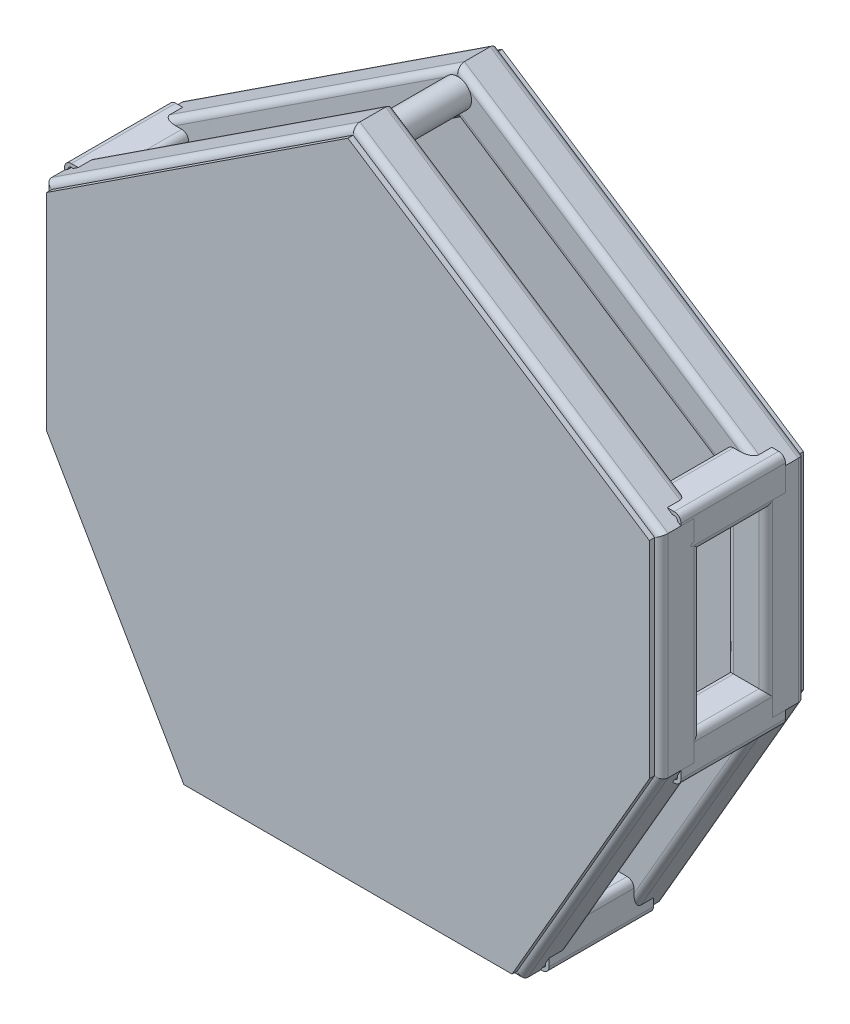
SolidWorks part; units mm, degrees
ref_plane "Front Plane" through (0, 0, 0) normal (0, 0, 1) x (1, 0, 0)
ref_plane "Top Plane" through (0, 0, 0) normal (0, 1, 0) x (1, 0, 0)
ref_plane "Right Plane" through (0, 0, 0) normal (1, 0, 0) x (0, 0, -1)
sketch "Sketch2" plane through (0, 0, 0) normal (0, 0, 1) x (1, 0, 0)
  line L7 (-356.066, 268.7117) -> (-135.0297, 413.7117)
  line L8 (-15.0297, -56.2883) -> (-255.0297, -56.2883)
  line L9 (86.0066, 118.7117) -> (86.0066, 268.7117)
  line L11 (-356.066, 118.7117) -> (-356.066, 268.7117)
  line L12 (-135.0297, 413.7117) -> (86.0066, 268.7117)
  line L13 (86.0066, 268.7117) -> (86.0066, 118.7117)
  line L14 (86.0066, 118.7117) -> (-15.0297, -56.2883)
  line L15 (-356.066, 268.7117) -> (-356.066, 118.7117)
  line L16 (-356.066, 118.7117) -> (-255.0297, -56.2883)
  dimension "D1" = 175
  dimension "D2" = 175
  dimension "D3" = 60
  dimension "D4" = 60
  dimension "D5" = 240
  dimension "D6" = 101.0363
  dimension "D7" = 150
  dimension "D8" = 150
  dimension "D9" = 470
ref_plane "Plane1" through (0, 0, 80) normal (0, 0, 1) x (1, 0, 0)
sketch "Sketch3" plane through (0, 0, 80) normal (0, 0, 1) x (1, 0, 0)
  line L0 (-135.0297, 413.7117) -> (86.0066, 268.7117) construction
  line L1 (86.0066, 118.7117) -> (86.0066, 268.7117) construction
  line L2 (86.0066, 118.7117) -> (-15.0297, -56.2883) construction
  line L3 (-15.0297, -56.2883) -> (-255.0297, -56.2883) construction
  line L4 (-356.066, 118.7117) -> (-255.0297, -56.2883) construction
  line L5 (-356.066, 118.7117) -> (-356.066, 268.7117) construction
  line L6 (-356.066, 268.7117) -> (-135.0297, 413.7117) construction
  line L7 (-135.0297, 413.7117) -> (86.0066, 268.7117)
  line L8 (86.0066, 118.7117) -> (86.0066, 268.7117)
  line L9 (86.0066, 118.7117) -> (-15.0297, -56.2883)
  line L10 (-15.0297, -56.2883) -> (-255.0297, -56.2883)
  line L11 (-356.066, 118.7117) -> (-255.0297, -56.2883)
  line L12 (-356.066, 118.7117) -> (-356.066, 268.7117)
  line L13 (-356.066, 268.7117) -> (-135.0297, 413.7117)
  dimension "D1" = 175
sketch3d "3DSketch1"
  line L0 (-356.066, 268.7117, 80) -> (-356.066, 268.7117, 0)
  line L1 (-356.066, 268.7117, 80) -> (-135.0297, 413.7117, 80) construction
  line L2 (-356.066, 118.7117, 80) -> (-356.066, 268.7117, 80) construction
  line L3 (-356.066, 118.7117, 0) -> (-356.066, 268.7117, 0) construction
  line L6 (86.0066, 118.7117, 0) -> (86.0066, 118.7117, 80)
  line L7 (-15.0297, -56.2883, 80) -> (-15.0297, -56.2883, 0)
  line L8 (-356.066, 118.7117, 80) -> (-356.066, 118.7117, 0)
  line L9 (86.0066, 268.7117, 80) -> (86.0066, 268.7117, 0)
  line L10 (-255.0297, -56.2883, 80) -> (-255.0297, -56.2883, 0)
  line L11 (-135.0297, 413.7117, 0) -> (-135.0297, 413.7117, 80)
other "Square tube 30 X 30 X 2.6(1)"
ref_plane "Plane2" through (-15.0297, -56.2883, 80) normal (-1, 0, 0) x (0, -1, 0)
sketch "Sketch1" plane through (-15.0297, -56.2883, 80) normal (-1, 0, 0) x (0, -1, 0)
  line L0 (-9.8, -12.4) -> (9.8, -12.4)
  line L1 (-12.4, -9.8) -> (-12.4, 9.8)
  line L2 (9.8, 12.4) -> (-9.8, 12.4)
  line L3 (12.4, 9.8) -> (12.4, -9.8)
  line L4 (-9.8, -15) -> (9.8, -15)
  line L5 (-15, -9.8) -> (-15, 9.8)
  line L6 (9.8, 15) -> (-9.8, 15)
  line L7 (15, 9.8) -> (15, -9.8)
  arc A0 (15, 9.8) -> (9.8, 15) centre (9.8, 9.8) ccw
  arc A1 (9.8, -15) -> (15, -9.8) centre (9.8, -9.8) ccw
  arc A2 (-15, -9.8) -> (-9.8, -15) centre (-9.8, -9.8) ccw
  arc A3 (-9.8, 15) -> (-15, 9.8) centre (-9.8, 9.8) ccw
  arc A4 (-9.8, 12.4) -> (-12.4, 9.8) centre (-9.8, 9.8) ccw
  arc A5 (12.4, 9.8) -> (9.8, 12.4) centre (9.8, 9.8) ccw
  arc A6 (9.8, -12.4) -> (12.4, -9.8) centre (9.8, -9.8) ccw
  arc A7 (-12.4, -9.8) -> (-9.8, -12.4) centre (-9.8, -9.8) ccw
  point P0 (-15, 0)
  point P1 (15, 0)
  point P2 (0, 15)
  point P3 (0, -15)
  point P4 (0, 0)
  point P5 (-15, -15)
  point P6 (15, -15)
  point P7 (15, 15)
  point P8 (-15, 15)
  point P33 (0, 0)
  dimension "D1" = 5.2
  dimension "Thickness" = 2.6
  dimension "V_leg" = 30
other "Square tube 30 X 30 X 2.6(2)"
ref_plane "Plane3" through (-15.0297, -56.2883, 0) normal (-1, 0, 0) x (0, -1, 0)
sketch "Sketch11" plane through (-15.0297, -56.2883, 0) normal (-1, 0, 0) x (0, -1, 0)
  line L0 (-9.8, -12.4) -> (9.8, -12.4)
  line L1 (-12.4, -9.8) -> (-12.4, 9.8)
  line L2 (9.8, 12.4) -> (-9.8, 12.4)
  line L3 (12.4, 9.8) -> (12.4, -9.8)
  line L4 (-9.8, -15) -> (9.8, -15)
  line L5 (-15, -9.8) -> (-15, 9.8)
  line L6 (9.8, 15) -> (-9.8, 15)
  line L7 (15, 9.8) -> (15, -9.8)
  arc A0 (15, 9.8) -> (9.8, 15) centre (9.8, 9.8) ccw
  arc A1 (9.8, -15) -> (15, -9.8) centre (9.8, -9.8) ccw
  arc A2 (-15, -9.8) -> (-9.8, -15) centre (-9.8, -9.8) ccw
  arc A3 (-9.8, 15) -> (-15, 9.8) centre (-9.8, 9.8) ccw
  arc A4 (-9.8, 12.4) -> (-12.4, 9.8) centre (-9.8, 9.8) ccw
  arc A5 (12.4, 9.8) -> (9.8, 12.4) centre (9.8, 9.8) ccw
  arc A6 (9.8, -12.4) -> (12.4, -9.8) centre (9.8, -9.8) ccw
  arc A7 (-12.4, -9.8) -> (-9.8, -12.4) centre (-9.8, -9.8) ccw
  point P0 (-15, 0)
  point P1 (15, 0)
  point P2 (0, 15)
  point P3 (0, -15)
  point P4 (0, 0)
  point P5 (-15, -15)
  point P6 (15, -15)
  point P7 (15, 15)
  point P8 (-15, 15)
  point P33 (0, 0)
  dimension "D1" = 5.2
  dimension "Thickness" = 2.6
  dimension "V_leg" = 30
other "Square tube 30 X 30 X 2.6(3)"
ref_plane "Plane4" through (-356.066, 118.7117, 80) normal (0, 0, -1) x (1, 0, 0)
sketch "Sketch12" plane through (-356.066, 118.7117, 80) normal (0, 0, -1) x (1, 0, 0)
  line L0 (-9.8, -12.4) -> (9.8, -12.4)
  line L1 (-12.4, -9.8) -> (-12.4, 9.8)
  line L2 (9.8, 12.4) -> (-9.8, 12.4)
  line L3 (12.4, 9.8) -> (12.4, -9.8)
  line L4 (-9.8, -15) -> (9.8, -15)
  line L5 (-15, -9.8) -> (-15, 9.8)
  line L6 (9.8, 15) -> (-9.8, 15)
  line L7 (15, 9.8) -> (15, -9.8)
  arc A0 (15, 9.8) -> (9.8, 15) centre (9.8, 9.8) ccw
  arc A1 (9.8, -15) -> (15, -9.8) centre (9.8, -9.8) ccw
  arc A2 (-15, -9.8) -> (-9.8, -15) centre (-9.8, -9.8) ccw
  arc A3 (-9.8, 15) -> (-15, 9.8) centre (-9.8, 9.8) ccw
  arc A4 (-9.8, 12.4) -> (-12.4, 9.8) centre (-9.8, 9.8) ccw
  arc A5 (12.4, 9.8) -> (9.8, 12.4) centre (9.8, 9.8) ccw
  arc A6 (9.8, -12.4) -> (12.4, -9.8) centre (9.8, -9.8) ccw
  arc A7 (-12.4, -9.8) -> (-9.8, -12.4) centre (-9.8, -9.8) ccw
  point P0 (-15, 0)
  point P1 (15, 0)
  point P2 (0, 15)
  point P3 (0, -15)
  point P4 (0, 0)
  point P5 (-15, -15)
  point P6 (15, -15)
  point P7 (15, 15)
  point P8 (-15, 15)
  point P33 (0, 0)
  dimension "D1" = 5.2
  dimension "Thickness" = 2.6
  dimension "V_leg" = 30
sketch "Sketch14" plane through (0, 0, -15) normal (0, 0, -1) x (-1, 0, 0)
  line L0 (135.0297, 425.4322) -> (365.866, 274.0034) construction
  line L1 (365.866, 274.0034) -> (365.866, 116.0858) construction
  line L2 (365.866, 116.0858) -> (260.6878, -66.0883) construction
  line L3 (260.6878, -66.0883) -> (9.3717, -66.0883) construction
  line L4 (9.3717, -66.0883) -> (-95.8066, 116.0858) construction
  line L5 (-95.8066, 116.0858) -> (-95.8066, 274.0034) construction
  line L6 (-95.8066, 274.0034) -> (135.0297, 425.4322) construction
  line L7 (135.0297, 425.4322) -> (365.866, 274.0034)
  line L8 (365.866, 274.0034) -> (365.866, 116.0858)
  line L9 (365.866, 116.0858) -> (260.6878, -66.0883)
  line L10 (260.6878, -66.0883) -> (9.3717, -66.0883)
  line L11 (9.3717, -66.0883) -> (-95.8066, 116.0858)
  line L12 (-95.8066, 116.0858) -> (-95.8066, 274.0034)
  line L13 (-95.8066, 274.0034) -> (135.0297, 425.4322)
extrude "Boss-Extrude1" add sketch "Sketch14" along normal blind 4 separate body
sketch "Sketch15" plane through (0, 0, 95) normal (0, 0, 1) x (1, 0, 0)
  line L0 (95.8066, 274.0034) -> (-135.0297, 425.4322) construction
  line L1 (95.8066, 116.0858) -> (95.8066, 274.0034) construction
  line L2 (-9.3717, -66.0883) -> (95.8066, 116.0858) construction
  line L3 (-260.6878, -66.0883) -> (-9.3717, -66.0883) construction
  line L4 (-365.866, 116.0858) -> (-260.6878, -66.0883) construction
  line L5 (-365.866, 274.0034) -> (-365.866, 116.0858) construction
  line L6 (-135.0297, 425.4322) -> (-365.866, 274.0034) construction
  line L7 (95.8066, 274.0034) -> (-135.0297, 425.4322)
  line L8 (95.8066, 116.0858) -> (95.8066, 274.0034)
  line L9 (-9.3717, -66.0883) -> (95.8066, 116.0858)
  line L10 (-260.6878, -66.0883) -> (-9.3717, -66.0883)
  line L11 (-365.866, 116.0858) -> (-260.6878, -66.0883)
  line L12 (-365.866, 274.0034) -> (-365.866, 116.0858)
  line L13 (-135.0297, 425.4322) -> (-365.866, 274.0034)
extrude "Boss-Extrude2" add sketch "Sketch15" along normal blind 4 separate body
other "Pipe 21.3 X 2.3(4)"
ref_plane "Plane5" through (-135.0297, 413.7117, 0) normal (0, 0, 1) x (1, 0, 0)
sketch "Sketch17" plane through (-135.0297, 413.7117, 0) normal (0, 0, 1) x (1, 0, 0)
  circle A0 centre (0, 0) radius 8.35
  circle A1 centre (0, 0) radius 10.65
  point P3 (0, 10.65)
  point P5 (-10.65, 0)
  point P6 (0, -10.65)
  point P7 (10.65, 0)
  point P8 (0, 0)
  dimension "In_dia" = 16.7
  dimension "Out_dia" = 21.3
